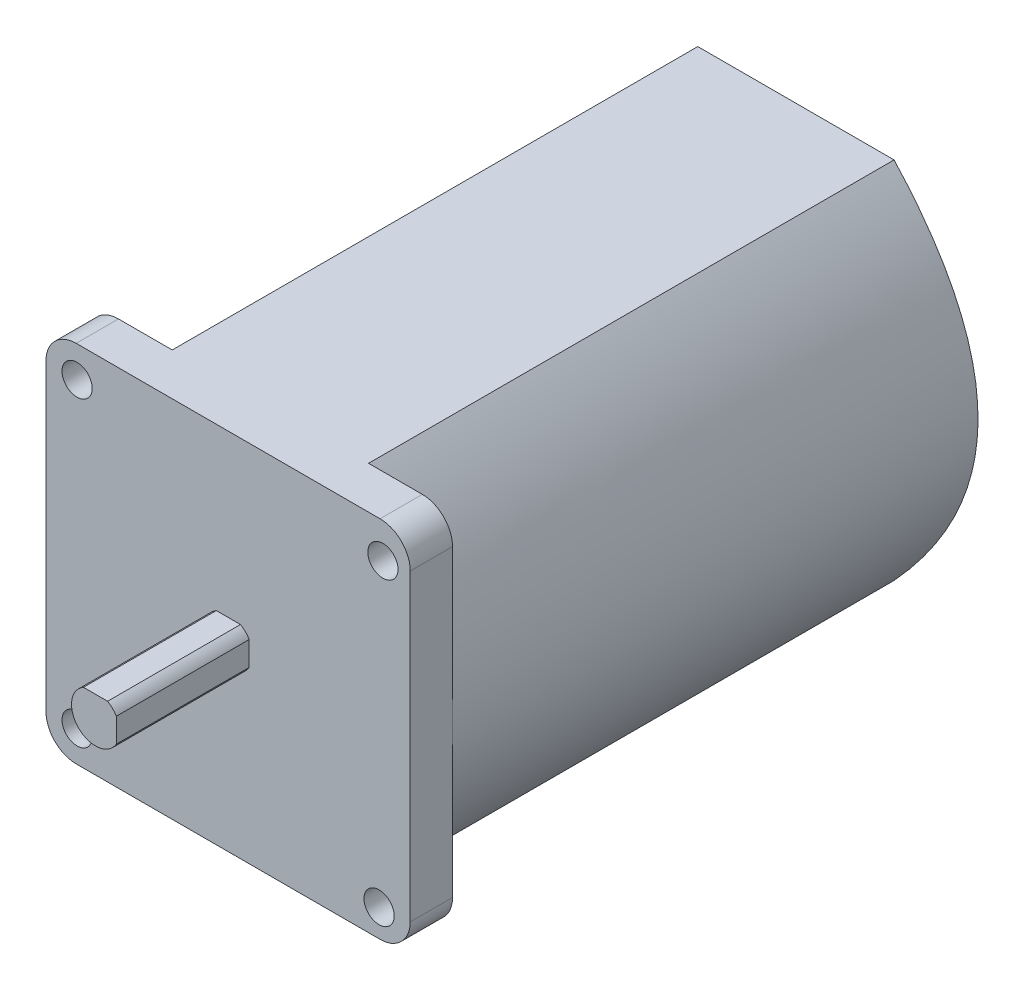
SolidWorks part; units mm, degrees
ref_plane "Front Plane" through (0, 0, 0) normal (0, 0, 1) x (1, 0, 0)
ref_plane "Top Plane" through (0, 0, 0) normal (0, 1, 0) x (1, 0, 0)
ref_plane "Right Plane" through (0, 0, 0) normal (1, 0, 0) x (0, 0, -1)
sketch "Sketch1" plane through (0, 0, 0) normal (0, 0, 1) x (1, 0, 0)
  line L1 (0, 0) -> (32.5, 0)
  line L3 (0, 60.3) -> (32.5, 60.3)
  spline S1 degree 2 poles (0, 60.3) (-27.8, 30.15) (0, 0) knots 0 0 0 1 1 1
  spline S2 degree 2 poles (32.5, 60.3) (60.3, 30.15) (32.5, 0) knots 0 0 0 1 1 1
extrude "Boss-Extrude1" add sketch "Sketch1" along normal blind 87
sketch "Sketch2" plane through (0, 0, 87) normal (0, 0, 1) x (1, 0, 0)
  line L0 (-13.9, 55.3) -> (-13.9, 5)
  line L4 (-8.9, 60.3) -> (41.4, 60.3)
  line L5 (46.4, 55.3) -> (46.4, 5)
  line L6 (41.4, 0) -> (-8.9, 0)
  circle A0 centre (-8.75, 55.15) radius 2.5
  circle A1 centre (-8.75, 5.15) radius 2.5
  circle A2 centre (41.246, 4.5188) radius 2.5
  circle A3 centre (41.8772, 54.5148) radius 2.5
  arc A4 (-8.9, 0) -> (-13.9, 5) centre (-8.9, 5) cw
  arc A5 (46.4, 5) -> (41.4, 0) centre (41.4, 5) cw
  arc A6 (41.4, 60.3) -> (46.4, 55.3) centre (41.4, 55.3) cw
  arc A7 (-13.9, 55.3) -> (-8.9, 60.3) centre (-8.9, 55.3) cw
  point P6 (16.25, 30.15)
  dimension "D1" = 5
extrude "Boss-Extrude2" add sketch "Sketch2" along normal blind 7
sketch "Sketch3" plane through (0, 0, 94) normal (0, 0, 1) x (1, 0, 0)
  line L6 (18.3001, 33.5852) -> (14.3001, 33.5852)
  line L8 (19.7353, 32.15) -> (19.7353, 28.15)
  arc A1 (18.3001, 33.5852) -> (19.7353, 32.15) centre (16.3001, 30.15) cw
  arc A2 (14.3001, 33.5852) -> (19.7353, 28.15) centre (16.3001, 30.15) ccw
extrude "Boss-Extrude3" add sketch "Sketch3" along normal blind 22
